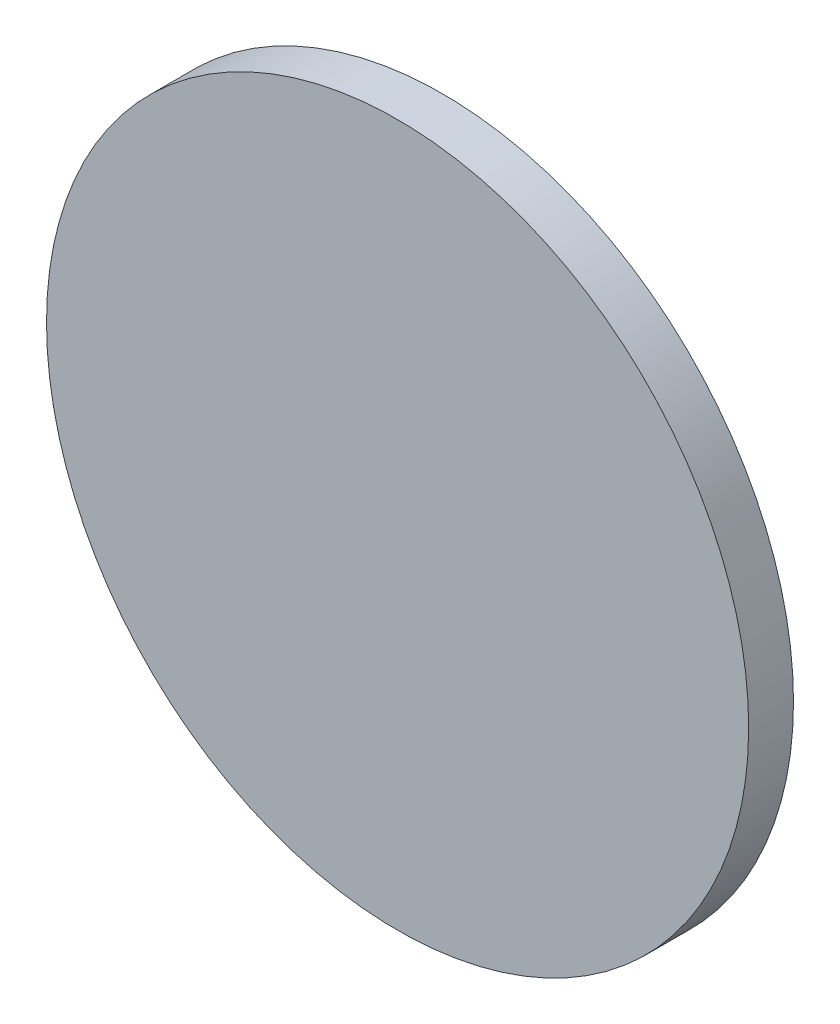
SolidWorks part; units mm, degrees
material "AISI 316 Stainless Steel Sheet (SS)"
ref_plane "Front Plane" through (0, 0, 0) normal (0, 0, 1) x (1, 0, 0)
ref_plane "Top Plane" through (0, 0, 0) normal (0, 1, 0) x (1, 0, 0)
ref_plane "Right Plane" through (0, 0, 0) normal (1, 0, 0) x (0, 0, -1)
sketch "Sketch1" plane through (0, 0, 0) normal (0, 0, 1) x (1, 0, 0)
  circle A0 centre (0, 0) radius 117.5
  dimension "D1" = 235
extrude "Boss-Extrude1" add sketch "Sketch1" along normal blind 15
